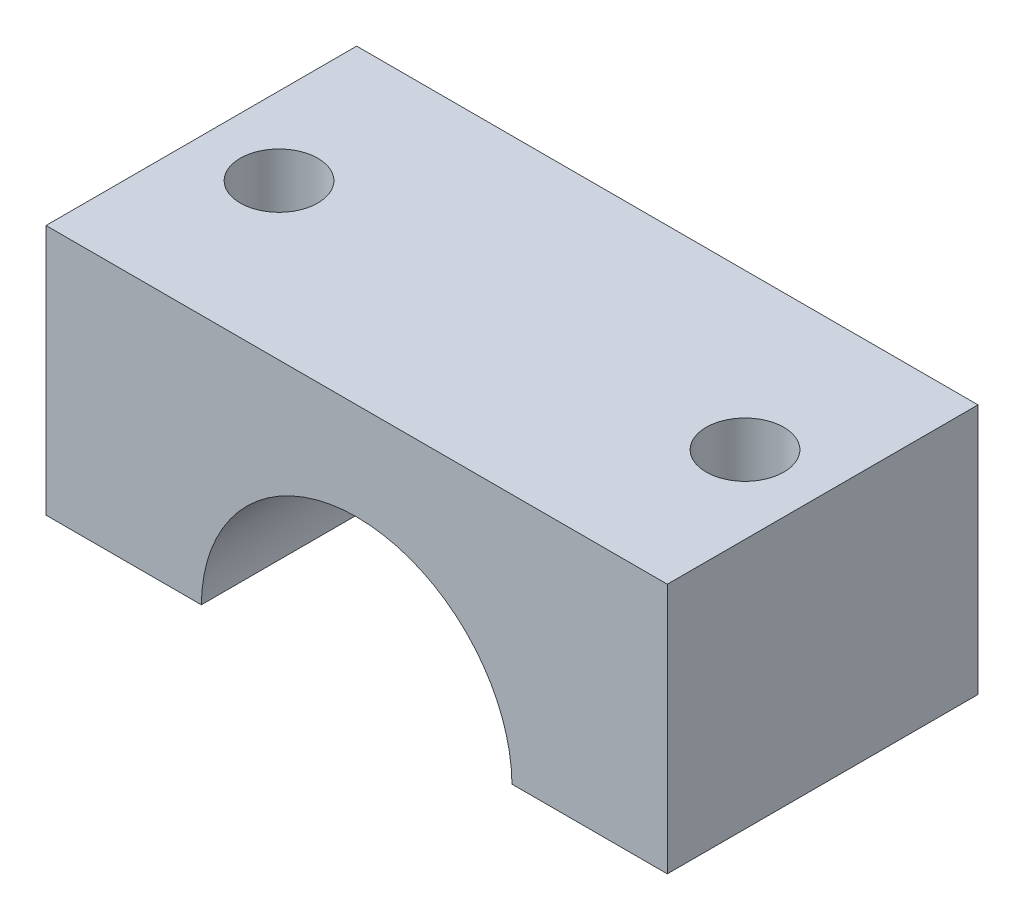
SolidWorks part; units mm, degrees
material "6061-T6 (SS)"
ref_plane "Front Plane" through (0, 0, 0) normal (0, 0, 1) x (1, 0, 0)
ref_plane "Top Plane" through (0, 0, 0) normal (0, 1, 0) x (1, 0, 0)
ref_plane "Right Plane" through (0, 0, 0) normal (1, 0, 0) x (0, 0, -1)
sketch "Sketch1" plane through (0, 0, 0) normal (0, 1, 0) x (1, 0, 0)
  line L1 (-25.4, -12.7) -> (25.4, -12.7)
  line L2 (-25.4, -12.7) -> (-25.4, 12.7)
  line L3 (-25.4, 12.7) -> (25.4, 12.7)
  line L4 (25.4, -12.7) -> (25.4, 12.7)
  line L5 (-25.4, -12.7) -> (25.4, 12.7) construction
  line L6 (-25.4, 12.7) -> (25.4, -12.7) construction
  point P0 (0, 0)
  dimension "D1" = 50.8
  dimension "D2" = 25.4
extrude "Block" add sketch "Sketch1" along normal blind 20.5105
sketch "Sketch3" plane through (0, 0, -12.7) normal (0, 0, -1) x (-1, 0, 0)
  circle A0 centre (0, -0.127) radius 12.7
  dimension "D2" = 25.4
  dimension "D1" = 0.127
extrude "Shaft Hole" cut sketch "Sketch3" against normal through all
sketch "Bolt Hole Pattern" plane through (0, 0, 0) normal (0, -1, 0) x (1, 0, 0)
  line L0 (0, 12.7) -> (0, -12.7) construction
  line L1 (12.6994, 12.7) -> (-12.6994, 12.7) construction
  line L2 (-12.6994, -12.7) -> (12.6994, -12.7) construction
  line L3 (25.4, 0) -> (-25.4, 0) construction
  line L4 (25.4, 12.7) -> (25.4, -12.7) construction
  line L5 (-25.4, -12.7) -> (-25.4, 12.7) construction
  point P0 (19.05, 0)
  point P1 (34.925, 0)
  point P9 (-19.05, 0)
  point P10 (-34.925, 0)
  point P17 (0, 0)
  dimension "D1" = 19.05
  dimension "D2" = 34.925
hole_wizard "Clamping Holes" positions "Sketch8" profile "Sketch7" hole size "1/4" standard "ANSI Inch" end condition through all
sketch "Sketch8" plane through (0, 0, 0) normal (0, -1, 0) x (-1, 0, 0)
  point P0 (-19.05, 0)
  point P3 (19.05, 0)
sketch "Sketch7" plane through (19.05, 0, 0) normal (1, 0, 0) x (0, 0, -1)
  line L0 (0, 0) -> (0, 20.5105)
  line L1 (0, 20.5105) -> (3.175, 20.5105)
  line L2 (3.175, 20.5105) -> (3.175, 0)
  line L5 (3.175, 0) -> (0, 0)
  line L11 (0, -6.35) -> (0, 107.95) construction
  dimension "Thru Hole Dia." = 6.35
  dimension "Thru Hole Depth" = 20.5105
